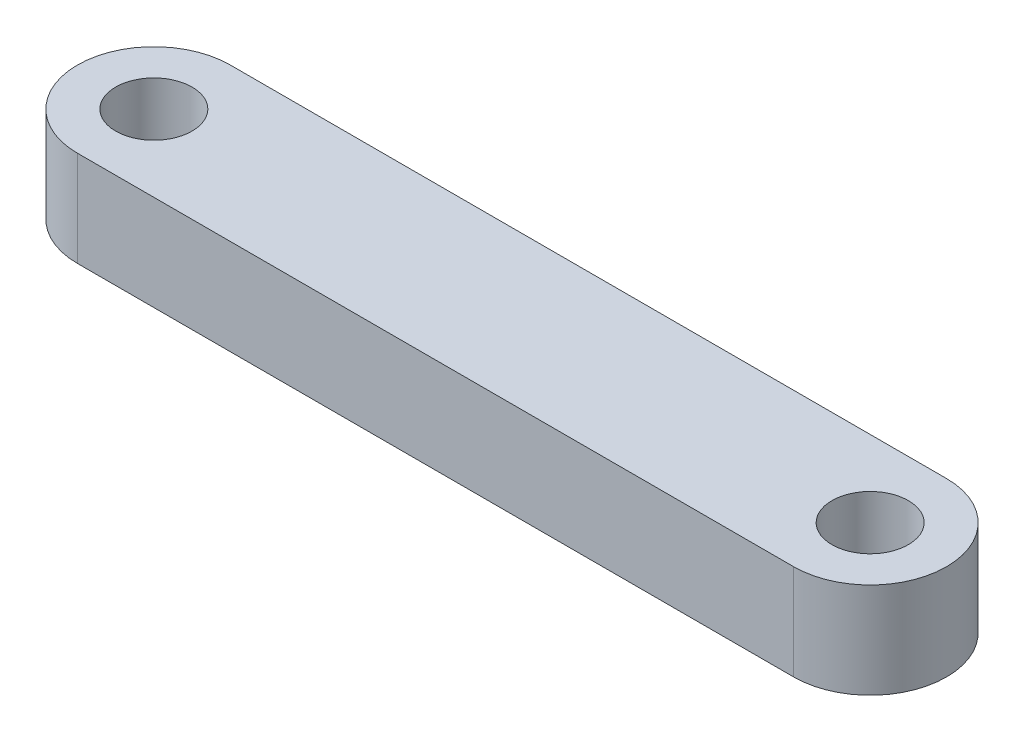
SolidWorks part; units mm, degrees
ref_plane "Front Plane" through (0, 0, 0) normal (0, 0, 1) x (1, 0, 0)
ref_plane "Top Plane" through (0, 0, 0) normal (0, 1, 0) x (1, 0, 0)
ref_plane "Right Plane" through (0, 0, 0) normal (1, 0, 0) x (0, 0, -1)
sketch "Sketch1" plane through (0, 0, 0) normal (0, 1, 0) x (1, 0, 0)
  line L0 (-130, 0) -> (-55, 0)
  line L1 (-130, -16) -> (-55, -16)
  arc A0 (-55, 0) -> (-55, -16) centre (-55, -8) cw
  arc A1 (-130, 0) -> (-130, -16) centre (-130, -8) ccw
  circle A2 centre (-130, -8) radius 4
  circle A3 centre (-55, -8) radius 4
extrude "Boss-Extrude1" add sketch "Sketch1" along normal blind 10
